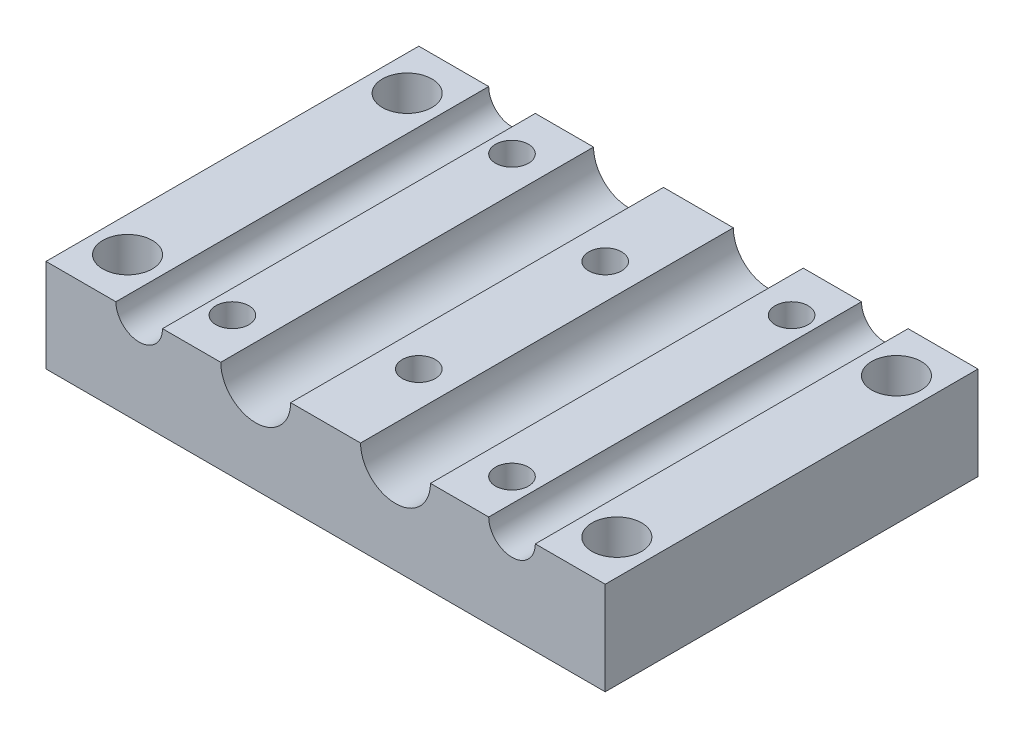
SolidWorks part; units mm, degrees
material "Copper"
ref_plane "Front Plane" through (0, 0, 0) normal (0, 0, 1) x (1, 0, 0)
ref_plane "Top Plane" through (0, 0, 0) normal (0, 1, 0) x (1, 0, 0)
ref_plane "Right Plane" through (0, 0, 0) normal (1, 0, 0) x (0, 0, -1)
sketch "Sketch1" plane through (0, 0, 0) normal (0, 1, 0) x (1, 0, 0)
  line L1 (-38.1, 25.4) -> (38.1, 25.4)
  line L2 (-38.1, 25.4) -> (-38.1, -25.4)
  line L3 (-38.1, -25.4) -> (38.1, -25.4)
  line L4 (38.1, 25.4) -> (38.1, -25.4)
  dimension "D1" = 50.8
  dimension "D2" = 76.2
  dimension "D3" = 38.1
  dimension "D4" = 25.4
extrude "Boss-Extrude1" add sketch "Sketch1" along normal blind 12.7
sketch "Sketch2" plane through (0, 0, 25.4) normal (0, 0, 1) x (1, 0, 0)
  line L0 (-38.1, 12.7) -> (38.1, 12.7) construction
  line L1 (-38.1, 12.7) -> (-38.1, 0) construction
  circle A0 centre (-25.4, 12.7) radius 3.175
  circle A1 centre (25.4, 12.7) radius 3.175
  dimension "D1" = 6.35
  dimension "D2" = 50.8
  dimension "D3" = 12.7
extrude "Cut-Extrude1" cut sketch "Sketch2" against normal through all
sketch "Sketch3" plane through (0, 0, 25.4) normal (0, 0, 1) x (1, 0, 0)
  line L0 (-22.225, 12.7) -> (22.225, 12.7) construction
  circle A0 centre (-9.525, 12.7) radius 4.7625
  circle A1 centre (9.525, 12.7) radius 4.7625
  dimension "D1" = 9.525
  dimension "D2" = 19.05
  dimension "D3" = 9.525
extrude "Cut-Extrude2" cut sketch "Sketch3" against normal through all
hole_wizard "1/4 Clearance Hole1" positions "Sketch5" profile "Sketch4" hole size "1/4" standard "ANSI Inch" end condition through all
sketch "Sketch5" plane through (0, 12.7, 0) normal (0, 1, 0) x (1, 0, 0)
  line L0 (-38.1, 25.4) -> (-38.1, -25.4) construction
  line L1 (-28.575, 25.4) -> (-38.1, 25.4) construction
  line L2 (-38.1, -25.4) -> (-28.575, -25.4) construction
  line L3 (38.1, -25.4) -> (38.1, 25.4) construction
  point P0 (-33.3375, -19.05)
  point P2 (-33.3375, 19.05)
  point P4 (33.3375, 19.05)
  point P6 (33.3375, -19.05)
  dimension "D1" = 4.7625
  dimension "D2" = 6.35
  dimension "D3" = 6.35
  dimension "D4" = 4.7625
sketch "Sketch4" plane through (-33.3375, 12.7, 19.05) normal (1, 0, 0) x (0, 0, 1)
  line L0 (0, 0) -> (0, 12.7)
  line L1 (0, 12.7) -> (3.3782, 12.7)
  line L2 (3.3782, 12.7) -> (3.3782, 0)
  line L5 (3.3782, 0) -> (0, 0)
  line L11 (0, -6.35) -> (0, 107.95) construction
  dimension "Thru Hole Dia." = 6.7564
  dimension "Thru Hole Depth" = 12.7
hole_wizard "#8 Clearance Hole1" positions "Sketch7" profile "Sketch6" hole size "#8" standard "ANSI Inch" end condition through all
sketch "Sketch7" plane through (0, 12.7, 0) normal (0, 1, 0) x (1, 0, 0)
  point P0 (-19.05, -19.05)
  point P2 (-19.05, 19.05)
  point P4 (0, 12.7)
  point P6 (0, -12.7)
  point P8 (19.05, -19.05)
  point P10 (19.05, 19.05)
  dimension "D1" = 19.05
  dimension "D2" = 12.7
  dimension "D3" = 12.7
  dimension "D4" = 19.05
  dimension "D5" = 38.1
  dimension "D6" = 19.05
sketch "Sketch6" plane through (-19.05, 12.7, 19.05) normal (1, 0, 0) x (0, 0, 1)
  line L0 (0, 0) -> (0, 12.7)
  line L1 (0, 12.7) -> (2.2479, 12.7)
  line L2 (2.2479, 12.7) -> (2.2479, 0)
  line L5 (2.2479, 0) -> (0, 0)
  line L11 (0, -6.35) -> (0, 107.95) construction
  dimension "Thru Hole Dia." = 4.4958
  dimension "Thru Hole Depth" = 12.7
sketch "Sketch8" plane through (0, 0, 0) normal (0, -1, 0) x (1, 0, 0)
  circle A0 centre (-19.05, 19.05) radius 6.096
  circle A1 centre (0, 12.7) radius 6.096
  circle A2 centre (19.05, 19.05) radius 6.096
  circle A3 centre (19.05, -19.05) radius 6.096
  circle A4 centre (-19.05, -19.05) radius 6.096
  circle A5 centre (0, -12.7) radius 6.096
  dimension "D1" = 12.192
extrude "Cut-Extrude3" cut sketch "Sketch8" against normal blind 3.175
